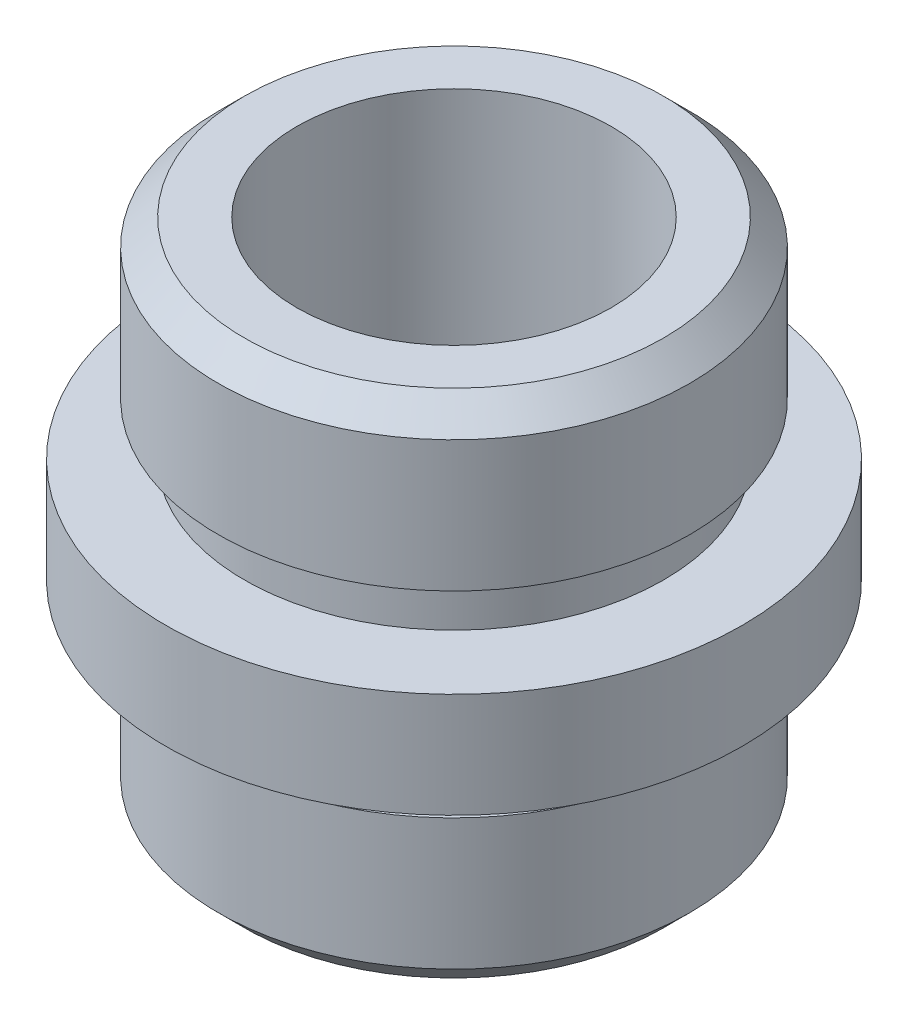
SolidWorks part; units mm, degrees
ref_plane "Front Plane" through (0, 0, 0) normal (0, 0, 1) x (1, 0, 0)
ref_plane "Top Plane" through (0, 0, 0) normal (0, 1, 0) x (1, 0, 0)
ref_plane "Right Plane" through (0, 0, 0) normal (1, 0, 0) x (0, 0, -1)
sketch "Sketch1" plane through (0, 0, 0) normal (0, 0, 1) x (1, 0, 0)
  line L0 (0, 26.9368) -> (0, -26.9368) construction
  line L1 (-12, -23) -> (-16, -23)
  line L2 (-18, -21) -> (-18, -11)
  line L3 (-18, -11) -> (-16, -11)
  line L4 (-16, -11) -> (-16, -8)
  line L5 (-16, -8) -> (-22, -8)
  line L6 (-22, -8) -> (-22, 0)
  line L7 (-22, 0) -> (-16, 0)
  line L8 (-16, 0) -> (-16, 4)
  line L9 (-16, 4) -> (-18, 4)
  line L10 (-18, 4) -> (-18, 14)
  line L11 (-16, 16) -> (-12, 16)
  line L12 (-16, -23) -> (-18, -21)
  line L13 (-18, 14) -> (-16, 16)
  line L14 (-12, 16) -> (-12, -23)
  point P4 (0, 0)
  point P5 (-18, -23)
  point P15 (-18, 16)
  dimension "D1" = 18
  dimension "D2" = 22
  dimension "D3" = 16
  dimension "D4" = 12
  dimension "D5" = 12
  dimension "D6" = 8
  dimension "D7" = 39
  dimension "D8" = 4
  dimension "D9" = 3
  dimension "D10" = 2
  dimension "D11" = 45
  dimension "D12" = 2
  dimension "D13" = 45
  dimension "D14" = 12
revolve "Revolve1" add sketch "Sketch1" angle 360 about L0
